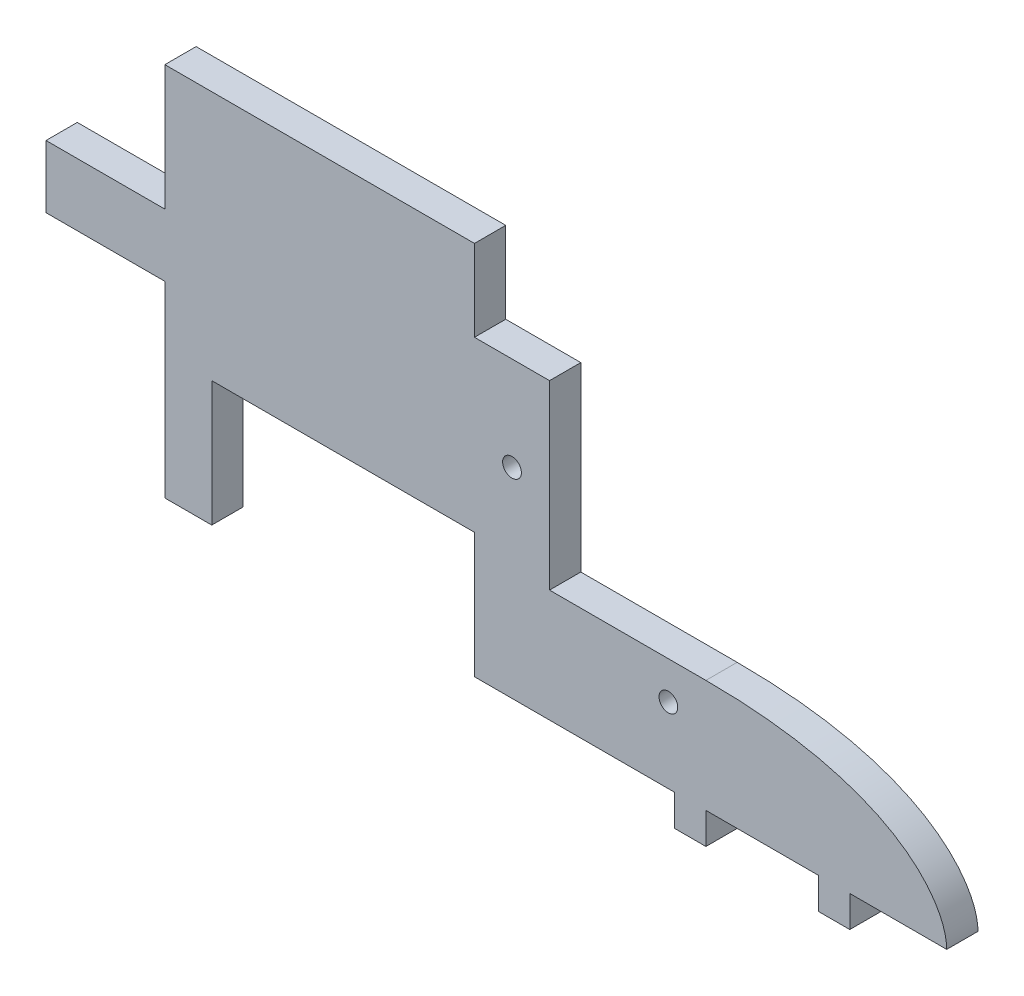
SolidWorks part; units mm, degrees
ref_plane "Plan de face" through (0, 0, 0) normal (0, 0, 1) x (1, 0, 0)
ref_plane "Plan de dessus" through (0, 0, 0) normal (0, 1, 0) x (1, 0, 0)
ref_plane "Plan de droite" through (0, 0, 0) normal (1, 0, 0) x (0, 0, -1)
sketch "Esquisse1" plane through (0, 0, 0) normal (0, 0, 1) x (1, 0, 0)
  line L1 (0, 0) -> (32, 0)
  line L2 (0, 0) -> (0, 47)
  line L3 (0, 47) -> (12, 47)
  line L4 (37, 0) -> (37, 18)
  line L6 (12, 47) -> (12, 18)
  line L7 (12, 18) -> (37, 18)
  line L8 (37, 0) -> (37, -5)
  line L9 (37, -5) -> (32, -5)
  line L10 (32, 0) -> (32, -5)
  circle A0 centre (6, 32) radius 1.5
  circle A1 centre (31, 12) radius 1.5
  dimension "D3" = 20
  dimension "D4" = 3
  dimension "D1" = 6
  dimension "D2" = 12
  dimension "D5" = 15
  dimension "D6" = 6
  dimension "D7" = 25
  dimension "D8" = 6
  dimension "D9" = 6
  dimension "D10" = 5
  dimension "D11" = 5
extrude "Boss.-Extru.1" add sketch "Esquisse1" along normal blind 5
sketch "Esquisse2" plane through (0, 0, 0) normal (0, 0, -1) x (-1, 0, 0)
  line L0 (-37, 18) -> (-12, 18) construction
  line L1 (-37, 0) -> (-55, 0)
  line L2 (-37, 0) -> (-37, 18)
  line L3 (-60, 0) -> (-75.5, 0)
  line L4 (42, 0) -> (49.5, 0)
  line L5 (0, 20) -> (0, 60)
  line L6 (0, 60) -> (20, 60)
  line L7 (-10, 167) -> (-1, 167)
  line L8 (0, 0) -> (-32, 0) construction
  line L9 (20, 60) -> (20, 90)
  line L10 (49.5, 120) -> (49.5, 142)
  line L11 (49.5, 0) -> (49.5, 30)
  line L12 (49.5, 30) -> (68.5, 30)
  line L14 (49.5, 40) -> (68.5, 40)
  line L15 (-60, 0) -> (-60, -5)
  line L16 (-60, -5) -> (-55, -5)
  line L17 (-55, 0) -> (-55, -5)
  line L18 (0, 20) -> (42, 20)
  line L19 (68.5, 30) -> (68.5, 40)
  line L20 (49.5, 120) -> (68.5, 120)
  line L21 (49.5, 40) -> (49.5, 110)
  line L22 (0, 47) -> (0, 0) construction
  line L23 (-20, 167) -> (-20, 172)
  line L24 (-20, 172) -> (-10, 172)
  line L25 (-10, 167) -> (-10, 172)
  line L26 (0, 0) -> (-32, 0) construction
  line L27 (42, 20) -> (42, 0)
  line L28 (49.5, 110) -> (68.5, 110)
  line L29 (-37, -5) -> (-37, 18) construction
  line L30 (-1, 167) -> (-1, 142)
  line L31 (20, 90) -> (-25, 90)
  line L32 (-1, 142) -> (49.5, 142)
  line L33 (-20, 167) -> (-25, 167)
  line L34 (-25, 90) -> (-25, 167)
  line L35 (68.5, 120) -> (68.5, 110)
  spline S0 degree 3 poles (-75.5, 0) (-75.5, 5.9822) (-67.6854, 18) (-37, 18) knots 0 0 0 0 1 1 1 1
  dimension "D1" = 38.5
  dimension "D2" = 20
  dimension "D3" = 167
  dimension "D4" = 49.5
  dimension "D5" = 5
  dimension "D6" = 30
  dimension "D7" = 10
  dimension "D8" = 10
  dimension "D9" = 30
  dimension "D10" = 70
  dimension "D11" = 19
  dimension "D12" = 5
  dimension "D13" = 42
  dimension "D14" = 20
  dimension "D15" = 40
  dimension "D16" = 45
  dimension "D17" = 5
  dimension "D19" = 25
  dimension "D21" = 24
extrude "Boss.-Extru.2" add sketch "Esquisse2" against normal blind 5
sketch "Esquisse3" plane through (0, 0, 0) normal (0, 0, -1) x (-1, 0, 0)
  line L0 (20, 60) -> (0, 60) construction
  line L1 (-49.1545, 182.2243) -> (187.1338, 182.2243)
  line L2 (-49.1545, 182.2243) -> (-49.1545, 60)
  line L3 (-49.1545, 60) -> (187.1338, 60)
  line L4 (187.1338, 182.2243) -> (187.1338, 60)
extrude "Enlèv. mat.-Extru.1" cut sketch "Esquisse3" against normal blind 5
